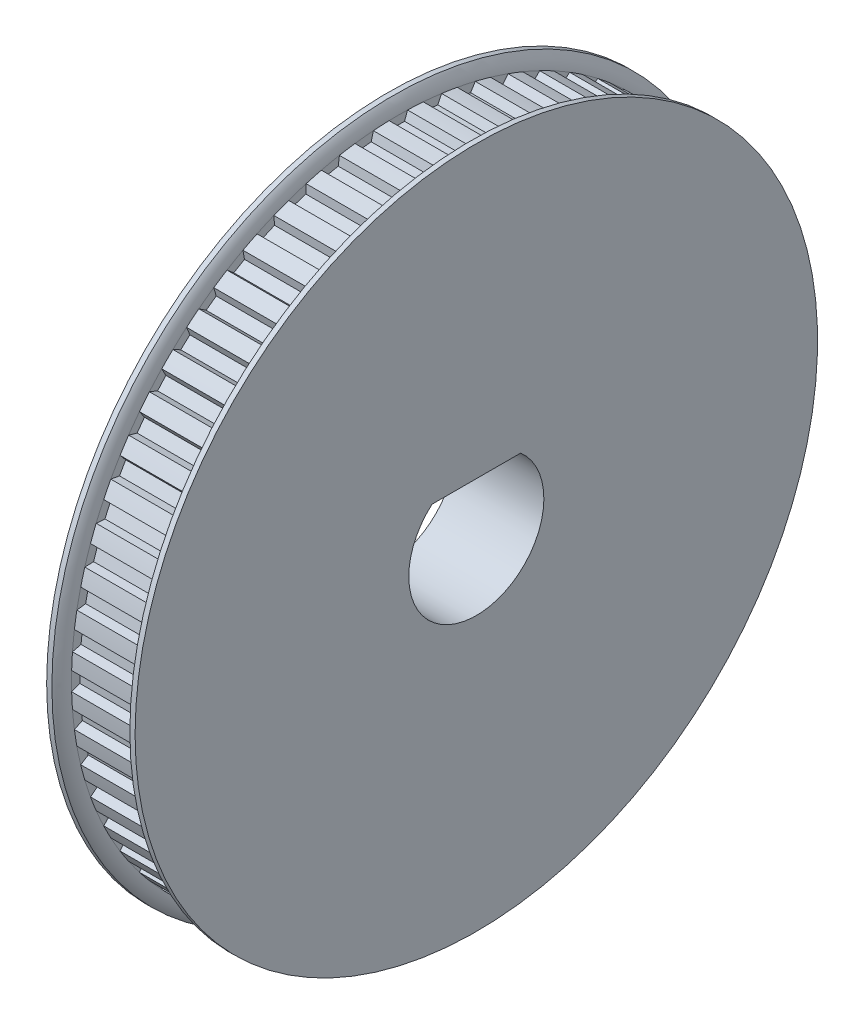
SolidWorks part; units mm, degrees
ref_plane "Front Plane" through (0, 0, 0) normal (0, 0, 1) x (1, 0, 0)
ref_plane "Top Plane" through (0, 0, 0) normal (0, 1, 0) x (1, 0, 0)
ref_plane "Right Plane" through (0, 0, 0) normal (1, 0, 0) x (0, 0, -1)
sketch "Sketch1" plane through (0, 0, 0) normal (1, 0, 0) x (0, 0, -1)
  line L3 (0, 0) -> (0, 49.725) construction
  line L6 (0, 49.725) -> (0, 50.925) construction
  line L7 (-1.325, 50.9078) -> (-0.8916, 49.717)
  line L8 (1.325, 50.9078) -> (0.8916, 49.717)
  line L9 (0, -2.2) -> (0, -3.2) construction
  line L10 (0, 51.425) -> (0, 50.925) construction
  line L12 (-0.8916, 49.717) -> (0.8916, 49.717)
  line L15 (0, 0) -> (0, -2.2) construction
  circle A0 centre (0, 0) radius 51.425 construction
  circle A1 centre (0, 0) radius 49.725 construction
  arc A7 (1.325, 50.9078) -> (-1.325, 50.9078) centre (0, 0) ccw
  dimension "PD" = 102.85
  dimension "D1" = 40
  dimension "D3" = 0.5
  dimension "D2" = 1.2
  dimension "D4" = 2.65
sketch "Sketch2" plane through (0, 0, 0) normal (0, 0, 1) x (1, 0, 0)
  line L0 (-10.5, 0) -> (10.5, 0) construction
  line L1 (-10.5, 4) -> (10.5, 4) construction
  line L2 (-10.5, 4) -> (-10.5, 19) construction
  line L3 (-2.2, 53) -> (-1.45, 53)
  line L4 (-0.7, 50.925) -> (-2.2, 50.925) construction
  line L5 (9.75, 50.925) -> (9.75, 53) construction
  line L6 (-0.7, 50.925) -> (9, 50.925)
  line L7 (-2.2, 19) -> (-2.2, 4)
  line L8 (9, 50.925) -> (10.5, 50.925) construction
  line L9 (9.75, 53) -> (10.5, 53)
  line L10 (10.5, 53) -> (10.5, 4)
  line L11 (-2.2, 4) -> (10.5, 4)
  line L12 (-6.35, 19) -> (-6.35, 4) construction
  line L13 (-2.2, 53) -> (-2.2, 19)
  line L14 (-2.2, 19) -> (-10.5, 19) construction
  arc A0 (9, 50.925) -> (9.75, 53) centre (12.2454, 50.925) cw
  arc A1 (-0.7, 50.925) -> (-1.45, 53) centre (-3.9454, 50.925) ccw
  point P19 (-0.7, 50.925)
  point P20 (9, 50.925)
  dimension "Bore Size" = 4
  dimension "Overall Width" = 21
  dimension "Inside Width" = 9.7
  dimension "Outside Width" = 12.7
  dimension "Hub Dia" = 19
  dimension "OD" = 106
sketch "Sketch6" plane through (0, 0, 0) normal (0, 0, 1) x (1, 0, 0)
  line L0 (9.75, 53) -> (10.5, 53) construction
  line L1 (-0.7, 50.925) -> (9, 50.925) construction
  line L2 (-2.2, 53) -> (-1.45, 53) construction
  line L3 (-2.2, 53) -> (-2.2, 19) construction
  line L4 (-2.2, 19) -> (-10.5, 19) construction
  line L5 (-10.5, 4) -> (-10.5, 19) construction
  line L6 (-10.5, 4) -> (10.5, 4) construction
  line L7 (10.5, 53) -> (10.5, 4) construction
  line L8 (9.75, 53) -> (10.5, 53)
  line L9 (-0.7, 50.925) -> (9, 50.925)
  line L10 (-2.2, 53) -> (-1.45, 53)
  line L11 (-2.2, 53) -> (-2.2, 19)
  line L12 (-2.2, 19) -> (-10.5, 19)
  line L13 (-10.5, 4) -> (-10.5, 19)
  line L14 (-10.5, 4) -> (10.5, 4)
  line L15 (10.5, 53) -> (10.5, 4)
  line L16 (-2.2, 19) -> (-2.2, 4)
  arc A0 (9.75, 53) -> (9, 50.925) centre (12.2454, 50.925) ccw construction
  arc A1 (-0.7, 50.925) -> (-1.45, 53) centre (-3.9454, 50.925) ccw construction
  arc A2 (9.75, 53) -> (9, 50.925) centre (12.2454, 50.925) ccw
  arc A3 (-0.7, 50.925) -> (-1.45, 53) centre (-3.9454, 50.925) ccw
revolve "Revolve1" add sketch "Sketch6" angle 360 about L14
sketch "Sketch3" plane through (0, 0, 0) normal (1, 0, 0) x (0, 0, -1)
  line L2 (-1.325, 50.9078) -> (-0.8916, 49.717) construction
  line L3 (-0.8916, 49.717) -> (0.8916, 49.717) construction
  line L4 (1.325, 50.9078) -> (0.8916, 49.717) construction
  line L5 (-1.325, 50.9078) -> (-0.8916, 49.717)
  line L6 (-0.8916, 49.717) -> (0.8916, 49.717)
  line L7 (1.325, 50.9078) -> (0.8916, 49.717)
  arc A1 (1.325, 50.9078) -> (-1.325, 50.9078) centre (0, 0) ccw construction
  arc A2 (1.325, 50.9078) -> (-1.325, 50.9078) centre (0, 0) ccw
extrude "Cut-Extrude1" cut sketch "Sketch3" along normal up to vertex (12 mm away) from vertex
pattern_circular "CirPattern1" count 60 over 360 about axis through (0, 4, 0) along (1, 0, 0) of "Cut-Extrude1"
sketch "Sketch5" plane through (0, 0, 0) normal (0, 0, 1) x (1, 0, 0)
  line L0 (-10.5, 0) -> (10.5, 0) construction
  point P0 (9, 0)
sketch "Sketch8" plane through (-2.2, 0, 0) normal (-1, 0, 0) x (0, 0, 1)
  line L0 (-6.3617, 11.3225) -> (6.3617, 11.3225)
  arc A0 (-6.3617, 11.3225) -> (6.3617, 11.3225) centre (0, 4) ccw
  circle A1 centre (0, 4) radius 49 construction
  dimension "D1" = 19.4
  dimension "D2" = 7.3225
extrude "Cut-Extrude2" cut sketch "Sketch8" against normal through all
equation "\"D3@Sketch1\" = \"ht@Sketch1\" / 2"
equation "\"D2@Sketch1\" = \"hs@Sketch1\" - \"ht@Sketch1\""
